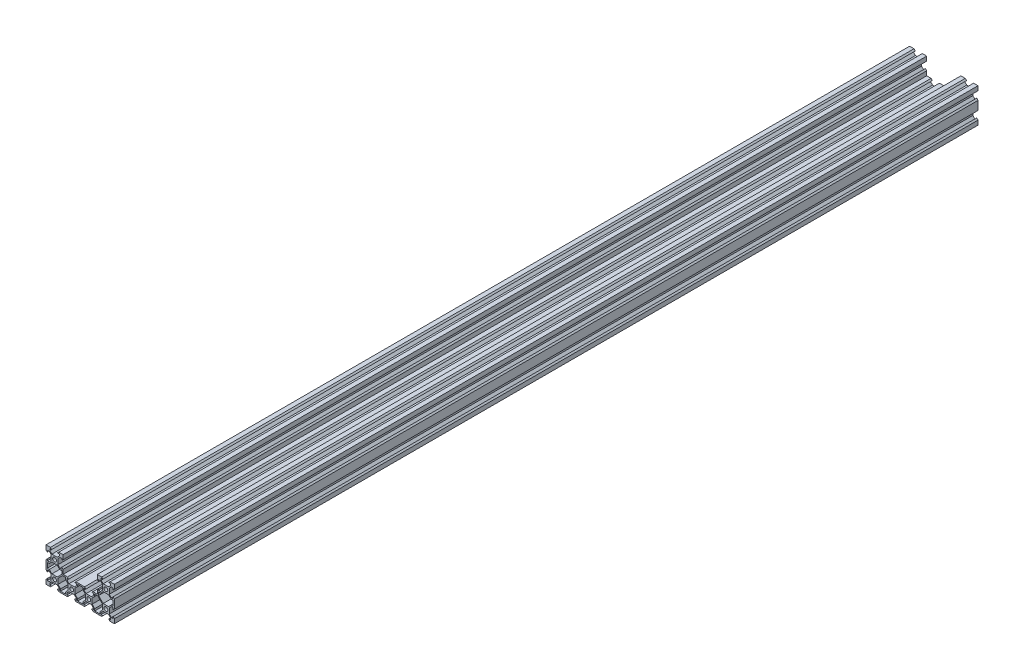
SolidWorks part; units mm, degrees
ref_plane "Front Plane" through (0, 0, 0) normal (0, 0, 1) x (1, 0, 0)
ref_plane "Top Plane" through (0, 0, 0) normal (0, 1, 0) x (1, 0, 0)
ref_plane "Right Plane" through (0, 0, 0) normal (1, 0, 0) x (0, 0, -1)
sketch "Sketch2" plane through (0, 0, 0) normal (0, 0, 1) x (1, 0, 0)
  line L0 (0, 10) -> (0, -10) construction
  line L1 (0, -10) -> (-40, -10)
  line L2 (-40, -10) -> (-40, 30)
  line L3 (-40, 30) -> (-20, 30)
  line L4 (-20, 30) -> (-20, 10)
  line L5 (-20, 10) -> (0, 10)
  line L6 (-20, 10) -> (-40, -10) construction
  line L7 (-20, 10) -> (0, -10) construction
  line L8 (0, 10) -> (-20, -10) construction
  line L9 (-20, -10) -> (-40, 10) construction
  line L10 (-40, 10) -> (-20, 30) construction
  line L11 (-20, 30) -> (-19.842, 30.1306) construction
  line L12 (-40, 30) -> (-20, 10) construction
  line L13 (-35.5, 28.5) -> (-35.5, 25.5)
  line L14 (-40, 24.875) -> (-38.5, 23.375)
  line L15 (-40, 20) -> (-20, 20) construction
  line L16 (-40, 15.125) -> (-38.5, 16.625)
  line L17 (-30, 30) -> (-30, -10) construction
  line L18 (-33.375, 28.5) -> (-35.5, 28.5)
  line L19 (-38.5, 25.5) -> (-35.5, 25.5)
  line L20 (-34.875, 30) -> (-33.375, 28.5)
  line L21 (-38.5, 23.375) -> (-38.5, 25.5)
  line L22 (-38.5, 16.625) -> (-38.5, 14.5)
  line L23 (-38.5, 14.5) -> (-35.5, 14.5)
  line L24 (-25.125, 30) -> (-26.625, 28.5)
  line L25 (-26.625, 28.5) -> (-24.5, 28.5)
  line L26 (-20, 24.875) -> (-21.5, 23.375)
  line L27 (-21.5, 23.375) -> (-21.5, 25.5)
  line L28 (-21.5, 25.5) -> (-24.5, 25.5)
  line L29 (-24.5, 28.5) -> (-24.5, 25.5)
  line L30 (-20, 15.125) -> (-21.5, 16.625)
  line L31 (-21.5, 16.625) -> (-21.5, 14.5)
  line L32 (-21.5, 14.5) -> (-24.5, 14.5)
  line L33 (-40, 4.875) -> (-38.5, 3.375)
  line L34 (-38.5, 3.375) -> (-38.5, 5.5)
  line L35 (-38.5, 5.5) -> (-35.5, 5.5)
  line L36 (-25.125, -10) -> (-26.625, -8.5)
  line L37 (-26.625, -8.5) -> (-24.5, -8.5)
  line L38 (-24.5, -8.5) -> (-24.5, -5.5)
  line L39 (-34.875, -10) -> (-33.375, -8.5)
  line L40 (-35.5, -8.5) -> (-35.5, -5.5)
  line L41 (-33.375, -8.5) -> (-35.5, -8.5)
  line L42 (-40, -4.875) -> (-38.5, -3.375)
  line L43 (-38.5, -3.375) -> (-38.5, -5.5)
  line L44 (-38.5, -5.5) -> (-35.5, -5.5)
  line L45 (-26, 24) -> (-34, 24)
  line L46 (-26, 24) -> (-26, 16)
  line L47 (-34, 24) -> (-34, 16)
  line L48 (-34, 16) -> (-26, 16)
  line L49 (-35.5, 26.3839) -> (-33.1161, 24)
  line L50 (-36.3839, 25.5) -> (-34, 23.1161)
  line L51 (-23.6161, 25.5) -> (-26, 23.1161)
  line L52 (-24.5, 26.3839) -> (-26.8839, 24)
  line L53 (-23.6161, 14.5) -> (-26, 16.8839)
  line L54 (-38.5, 13) -> (-38.5, 7)
  line L55 (-38.5, 13) -> (-36.1161, 13)
  line L56 (-36.3839, 14.5) -> (-34, 16.8839)
  line L57 (-36.1161, 13) -> (-33.1161, 16)
  line L58 (-38.5, 7) -> (-36.1161, 7)
  line L59 (-36.1161, 7) -> (-33.1161, 4)
  line L60 (-26, -4) -> (-34, -4)
  line L61 (-34, -4) -> (-34, 4)
  line L62 (-26, -4) -> (-26, 4)
  line L63 (-34, 4) -> (-26, 4)
  line L64 (-26.891, 4) -> (-21.5, 9.391)
  line L65 (-23.8839, 13) -> (-26.8839, 16)
  line L66 (-21.5, 13) -> (-23.8839, 13)
  line L67 (-21.5, 13) -> (-21.5, 9.391)
  line L68 (-23, -6.1161) -> (-26, -3.1161)
  line L69 (-23, -8.5) -> (-23, -6.1161)
  line L70 (-17, -8.5) -> (-23, -8.5)
  line L71 (-17, -8.5) -> (-17, -6.1161)
  line L72 (-17, -6.1161) -> (-14, -3.1161)
  line L73 (-17, 6.1161) -> (-14, 3.1161)
  line L74 (-17, 8.5) -> (-17, 6.1161)
  line L75 (-17, 8.5) -> (-20.609, 8.5)
  line L76 (-26, 3.109) -> (-20.609, 8.5)
  line L77 (-36.3839, 5.5) -> (-34, 3.1161)
  line L78 (-36.3839, -5.5) -> (-34, -3.1161)
  line L79 (-35.5, -6.3839) -> (-33.1161, -4)
  line L80 (-24.5, -6.3839) -> (-26.8839, -4)
  line L81 (-5.125, 10) -> (-6.625, 8.5)
  line L82 (-4.5, 8.5) -> (-4.5, 5.5)
  line L83 (-6.625, 8.5) -> (-4.5, 8.5)
  line L84 (-4.5, 6.3839) -> (-6.8839, 4)
  line L85 (14.875, -10) -> (13.375, -8.5)
  line L86 (-15.5, -8.5) -> (-15.5, -5.5)
  line L87 (-14.875, -10) -> (-13.375, -8.5)
  line L88 (-13.375, -8.5) -> (-15.5, -8.5)
  line L89 (13.375, -8.5) -> (15.5, -8.5)
  line L90 (15.5, -8.5) -> (15.5, -5.5)
  line L91 (-5.125, -10) -> (-6.625, -8.5)
  line L92 (-6.625, -8.5) -> (-4.5, -8.5)
  line L93 (-4.5, -8.5) -> (-4.5, -5.5)
  line L94 (-15.5, -6.3839) -> (-13.1161, -4)
  line L95 (15.5, -6.3839) -> (13.1161, -4)
  line L96 (4.5, -6.3839) -> (6.8839, -4)
  line L97 (-4.5, -6.3839) -> (-6.8839, -4)
  line L98 (-6, -4) -> (-6, 4)
  line L99 (-14, -4) -> (-6, -4)
  line L100 (-14, -4) -> (-14, 4)
  line L101 (-6, 4) -> (-14, 4)
  line L102 (0, 0) -> (-40, 0) construction
  line L103 (-15.5, 6.3839) -> (-13.1161, 4)
  line L104 (-15.5, 8.5) -> (-15.5, 5.5)
  line L105 (-14.875, 10) -> (-13.375, 8.5)
  line L106 (-13.375, 8.5) -> (-15.5, 8.5)
  line L107 (-10, 10) -> (-10, -10) construction
  line L108 (4.5, -8.5) -> (4.5, -5.5)
  line L109 (6.625, -8.5) -> (4.5, -8.5)
  line L110 (5.125, -10) -> (6.625, -8.5)
  line L111 (17, 8.5) -> (20.609, 8.5)
  line L112 (17, 8.5) -> (17, 6.1161)
  line L113 (17, 6.1161) -> (14, 3.1161)
  line L114 (15.5, 6.3839) -> (13.1161, 4)
  line L115 (14.875, 10) -> (13.375, 8.5)
  line L116 (15.5, 8.5) -> (15.5, 5.5)
  line L117 (13.375, 8.5) -> (15.5, 8.5)
  line L118 (5.125, 10) -> (6.625, 8.5)
  line L119 (6.625, 8.5) -> (4.5, 8.5)
  line L120 (4.5, 8.5) -> (4.5, 5.5)
  line L121 (4.5, 6.3839) -> (6.8839, 4)
  line L122 (14, -4) -> (6, -4)
  line L123 (14, -4) -> (14, 4)
  line L124 (6, 4) -> (14, 4)
  line L125 (6, -4) -> (6, 4)
  line L126 (0, -10) -> (40, -10)
  line L127 (36.3839, 14.5) -> (34, 16.8839)
  line L128 (40, 15.125) -> (38.5, 16.625)
  line L129 (38.5, 16.625) -> (38.5, 14.5)
  line L130 (38.5, 14.5) -> (35.5, 14.5)
  line L131 (38.5, 7) -> (36.1161, 7)
  line L132 (38.5, 13) -> (38.5, 7)
  line L133 (40, 4.875) -> (38.5, 3.375)
  line L134 (38.5, 3.375) -> (38.5, 5.5)
  line L135 (38.5, 5.5) -> (35.5, 5.5)
  line L136 (36.3839, 5.5) -> (34, 3.1161)
  line L137 (36.1161, 7) -> (33.1161, 4)
  line L138 (38.5, 13) -> (36.1161, 13)
  line L139 (36.1161, 13) -> (33.1161, 16)
  line L140 (26, 24) -> (34, 24)
  line L141 (34, 24) -> (34, 16)
  line L142 (34, 16) -> (26, 16)
  line L143 (26, 24) -> (26, 16)
  line L144 (23.6161, 14.5) -> (26, 16.8839)
  line L145 (21.5, 16.625) -> (21.5, 14.5)
  line L146 (20, 15.125) -> (21.5, 16.625)
  line L147 (21.5, 14.5) -> (24.5, 14.5)
  line L148 (23.8839, 13) -> (26.8839, 16)
  line L149 (21.5, 13) -> (23.8839, 13)
  line L150 (21.5, 13) -> (21.5, 9.391)
  line L151 (26.891, 4) -> (21.5, 9.391)
  line L152 (26, 3.109) -> (20.609, 8.5)
  line L153 (38.5, -3.375) -> (38.5, -5.5)
  line L154 (40, -4.875) -> (38.5, -3.375)
  line L155 (36.3839, -5.5) -> (34, -3.1161)
  line L156 (38.5, -5.5) -> (35.5, -5.5)
  line L157 (35.5, -6.3839) -> (33.1161, -4)
  line L158 (35.5, -8.5) -> (35.5, -5.5)
  line L159 (34.875, -10) -> (33.375, -8.5)
  line L160 (33.375, -8.5) -> (35.5, -8.5)
  line L161 (34, 4) -> (26, 4)
  line L162 (34, -4) -> (34, 4)
  line L163 (26, -4) -> (34, -4)
  line L164 (26, -4) -> (26, 4)
  line L165 (23, -6.1161) -> (26, -3.1161)
  line L166 (23, -8.5) -> (23, -6.1161)
  line L167 (26.625, -8.5) -> (24.5, -8.5)
  line L168 (24.5, -8.5) -> (24.5, -5.5)
  line L169 (24.5, -6.3839) -> (26.8839, -4)
  line L170 (17, -6.1161) -> (14, -3.1161)
  line L171 (17, -8.5) -> (17, -6.1161)
  line L172 (17, -8.5) -> (23, -8.5)
  line L173 (40, -10) -> (40, 30)
  line L174 (36.3839, 25.5) -> (34, 23.1161)
  line L175 (35.5, 26.3839) -> (33.1161, 24)
  line L176 (40, 24.875) -> (38.5, 23.375)
  line L177 (38.5, 23.375) -> (38.5, 25.5)
  line L178 (38.5, 25.5) -> (35.5, 25.5)
  line L179 (35.5, 28.5) -> (35.5, 25.5)
  line L180 (33.375, 28.5) -> (35.5, 28.5)
  line L181 (34.875, 30) -> (33.375, 28.5)
  line L182 (25.125, 30) -> (26.625, 28.5)
  line L183 (26.625, 28.5) -> (24.5, 28.5)
  line L184 (24.5, 26.3839) -> (26.8839, 24)
  line L185 (24.5, 28.5) -> (24.5, 25.5)
  line L186 (23.6161, 25.5) -> (26, 23.1161)
  line L187 (21.5, 25.5) -> (24.5, 25.5)
  line L188 (21.5, 23.375) -> (21.5, 25.5)
  line L189 (20, 24.875) -> (21.5, 23.375)
  line L190 (40, 30) -> (20, 30)
  line L191 (0, 10) -> (20, 10)
  line L192 (20, 10) -> (20, 30)
  line L193 (3, 8.5) -> (-3, 8.5)
  line L194 (-3, 8.5) -> (-3, 6.1161)
  line L195 (-3, 6.1161) -> (-6, 3.1161)
  line L196 (3, 8.5) -> (3, 6.1161)
  line L197 (3, 6.1161) -> (6, 3.1161)
  line L198 (-3, -8.5) -> (-3, -6.1161)
  line L199 (-3, -6.1161) -> (-6, -3.1161)
  line L200 (3, -6.1161) -> (6, -3.1161)
  line L201 (3, -8.5) -> (3, -6.1161)
  line L202 (3, -8.5) -> (-3, -8.5)
  line L203 (25.125, -10) -> (26.625, -8.5)
  circle A0 centre (-30, 20) radius 2.25
  circle A1 centre (-30, 0) radius 2.25
  circle A2 centre (-10, 0) radius 2.25
  circle A3 centre (10, 0) radius 2.25
  circle A4 centre (30, 20) radius 2.25
  circle A5 centre (30, 0) radius 2.25
  point P3 (0, 0)
  point P75 (-38.5, 10)
  point P232 (25.125, -10)
  point P271 (0, 8.5)
  dimension "D8" = 4.5
  dimension "D1" = 40
  dimension "D2" = 40
  dimension "D3" = 20
  dimension "D4" = 4.5
  dimension "D5" = 3.375
  dimension "D6" = 1.5
  dimension "D7" = 8
  dimension "D9" = 0.625
  dimension "D10" = 0.625
  dimension "D11" = 1.5
  dimension "D12" = 0.63
  dimension "D13" = 40
  dimension "D14" = 40
  dimension "D15" = 20
  dimension "D16" = 3
  dimension "D17" = 1.5
  dimension "D18" = 0.625
extrude "Boss-Extrude1" add sketch "Sketch2" along normal blind 1010
